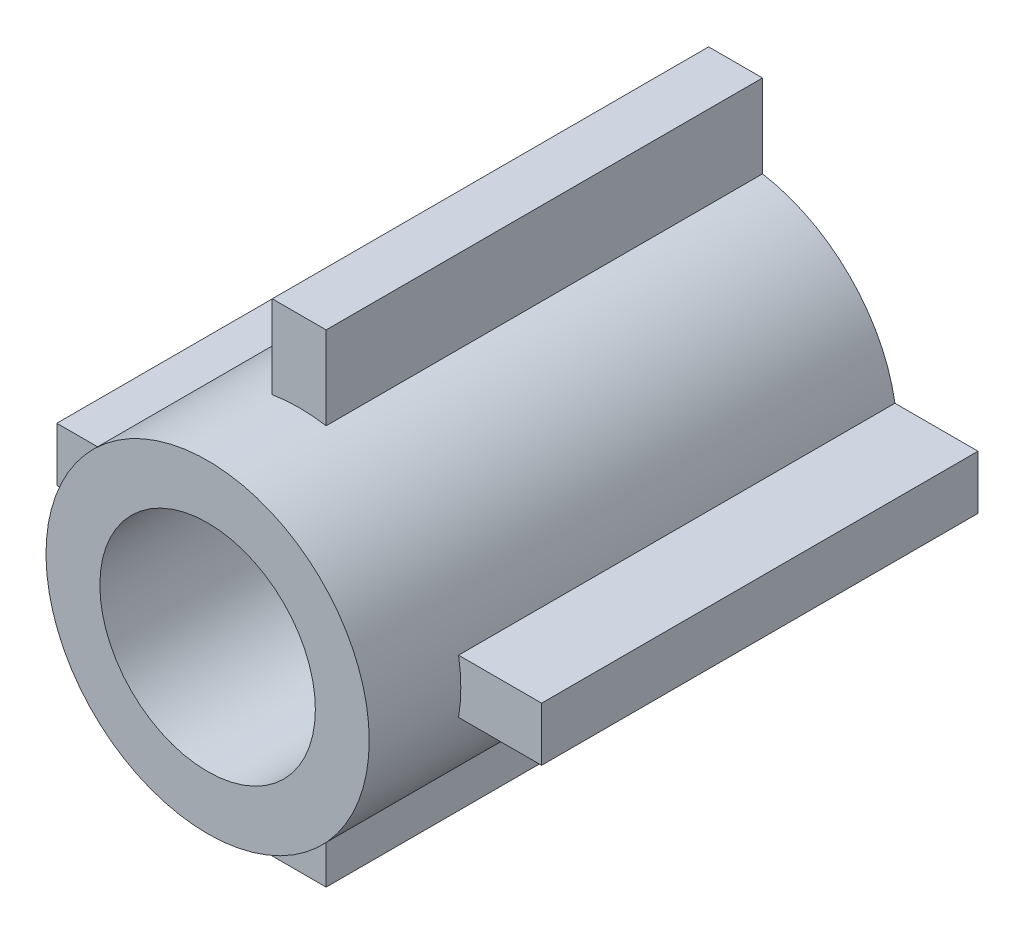
SolidWorks part; units mm, degrees
ref_plane "Plano frontal" through (0, 0, 0) normal (0, 0, 1) x (1, 0, 0)
ref_plane "Plano superior" through (0, 0, 0) normal (0, 1, 0) x (1, 0, 0)
ref_plane "Plano direito" through (0, 0, 0) normal (1, 0, 0) x (0, 0, -1)
sketch "Esboço1" plane through (0, 0, 0) normal (0, 0, 1) x (1, 0, 0)
  circle A0 centre (0, 0) radius 2
  circle A1 centre (0, 0) radius 3
  dimension "D1" = 4
  dimension "D2" = 6
extrude "Ressalto-extrusão1" add sketch "Esboço1" along normal blind 8.1
sketch "Esboço2" plane through (0, 0, 0) normal (0, 0, 1) x (1, 0, 0)
  line L5 (0, 0) -> (-3, 0)
  line L6 (-2.9988, 0.5) -> (-4.4988, 0.5)
  line L7 (-4.4988, 0.5) -> (-4.4988, -0.5)
  line L8 (-4.4988, -0.5) -> (-3, -0.5)
  line L10 (-2.9988, 0.5) -> (-2.958, 0.5)
  line L11 (-3, -0.5) -> (-2.958, -0.5)
  circle A1 centre (0, 0) radius 3 construction
  circle A2 centre (0, 0) radius 3
  dimension "D1" = 1.5
  dimension "D2" = 1
  dimension "D3" = 0.5
extrude "Ressalto-extrusão2" add sketch "Esboço2" along normal blind 8.1 contours A2 L10 L6 L7 L8 L11
sketch "Esboço3" plane through (0, 0, 0) normal (0, 0, -1) x (-1, 0, 0)
  line L0 (0, 0) -> (0, 3)
  line L1 (0, 3) -> (0, 0)
  line L2 (-3, 0) -> (0, 0)
  line L3 (0, 0) -> (0, -3)
  line L4 (0, -3) -> (0, 0)
  line L6 (-0.5, 3) -> (-0.5, 4.5)
  line L7 (-0.5, 4.5) -> (0.5, 4.5)
  line L8 (0.5, 4.5) -> (0.5, 3)
  line L10 (-0.5, 3) -> (-0.5, 2.958)
  line L11 (0.5, 3) -> (0.5, 2.958)
  line L13 (-3, 0.5) -> (-4.5, 0.5)
  line L14 (-4.5, 0.5) -> (-4.5, -0.5)
  line L15 (-4.5, -0.5) -> (-2.958, -0.5)
  line L16 (-3, 0.5) -> (-2.958, 0.5)
  line L17 (0.5, -3) -> (0.5, -2.958)
  line L18 (0.5, -3) -> (0.5, -4.458)
  line L19 (0.5, -4.458) -> (-0.5, -4.458)
  line L20 (-0.5, -4.458) -> (-0.5, -2.958)
  arc A0 (2.958, 0.5) -> (2.958, -0.5) centre (0, 0) ccw construction
  arc A1 (0.5, 2.958) -> (-0.5, 2.958) centre (0, 0) ccw
  arc A2 (-0.5, -2.958) -> (0.5, -2.958) centre (0, 0) ccw
  arc A3 (-2.958, 0.5) -> (-2.958, -0.5) centre (0, 0) ccw
  arc M9 (2.958, 0.5) -> (2.958, -0.5) centre (0, 0) ccw
  dimension "D1" = 1
  dimension "D2" = 1.5
  dimension "D3" = 0.5
  dimension "D4" = 1.5
  dimension "D5" = 0.5
  dimension "D6" = 1.5
  dimension "D7" = 0.5
extrude "Ressalto-extrusão3" add sketch "Esboço3" against normal blind 8.1 contours L20 L19 L18 L17 M9 | L16 L13 L14 L15 M9 | L8 L11 A1 L10 L6 L7
sketch "Esboço6" plane through (0, 0, 8.1) normal (0, 0, 1) x (1, 0, 0)
  line L0 (0.5, 2.958) -> (0.5, 4.5)
  line L1 (0.5, 4.5) -> (-0.4975, 4.5)
  line L2 (-0.4975, 4.5) -> (-0.4975, 2.9585)
  line L3 (-2.958, 0.5) -> (-4.5, 0.5)
  line L4 (-4.5, 0.5) -> (-4.5, -0.5)
  line L5 (-4.5, -0.5) -> (-2.958, -0.5)
  line L6 (-0.5, -2.958) -> (-0.5, -4.5)
  line L7 (-0.5, -4.5) -> (0.5, -4.5)
  line L8 (0.5, -4.5) -> (0.5, -2.958)
  line L9 (2.958, -0.5) -> (4.5, -0.5)
  line L10 (4.5, -0.5) -> (4.5, 0.5)
  line L11 (4.5, 0.5) -> (2.958, 0.5)
  circle A4 centre (0, 0) radius 3
  arc A5 (2.958, 0.5) -> (0.5, 2.958) centre (0, 0) ccw
  arc A6 (-0.4975, 2.9585) -> (-2.958, 0.5) centre (0, 0) ccw
  arc A7 (-2.958, -0.5) -> (-0.5, -2.958) centre (0, 0) ccw
  arc A8 (0.5, -2.958) -> (2.958, -0.5) centre (0, 0) ccw
  point P23 (0, 0)
  arc M1 (-2.958, -0.5) -> (-0.5, -2.958) centre (0, 0) ccw
  line M2 (-0.5, -2.958) -> (-0.5, -4.458)
  line M3 (-0.5, -4.458) -> (0.5, -4.458)
  line M4 (0.5, -4.458) -> (0.5, -2.958)
  arc M5 (0.5, -2.958) -> (2.958, -0.5) centre (0, 0) ccw
  line M6 (2.958, -0.5) -> (4.5, -0.5)
  line M7 (4.5, -0.5) -> (4.5, 0.5)
  line M8 (4.5, 0.5) -> (2.958, 0.5)
  arc M9 (2.958, 0.5) -> (0.5, 2.958) centre (0, 0) ccw
  line M10 (0.5, 2.958) -> (0.5, 4.5)
  line M11 (0.5, 4.5) -> (-0.5, 4.5)
  arc M13 (-0.5, 2.958) -> (-2.958, 0.5) centre (0, 0) ccw
  line M14 (-2.958, 0.5) -> (-4.4988, 0.5)
  line M15 (-4.4988, 0.5) -> (-4.4988, -0.5)
  line M16 (-4.4988, -0.5) -> (-2.958, -0.5)
  circle M17 centre (0, 0) radius 2
extrude "Ressalto-extrusão4" add sketch "Esboço6" against normal blind 8.1 contours A4 M9 M13 M1 M5 M17 | A4 L2 M10 M11 | A4 M6 M7 M8 | A4 M2 M3 M4 | A4 M14 M15 M16
sketch "Esboço7" plane through (0, 0, 8.1) normal (0, 0, 1) x (1, 0, 0)
  circle A0 centre (0, 0) radius 2
  circle A1 centre (0, 0) radius 3
extrude "Ressalto-extrusão5" add sketch "Esboço7" along normal blind 1.7
